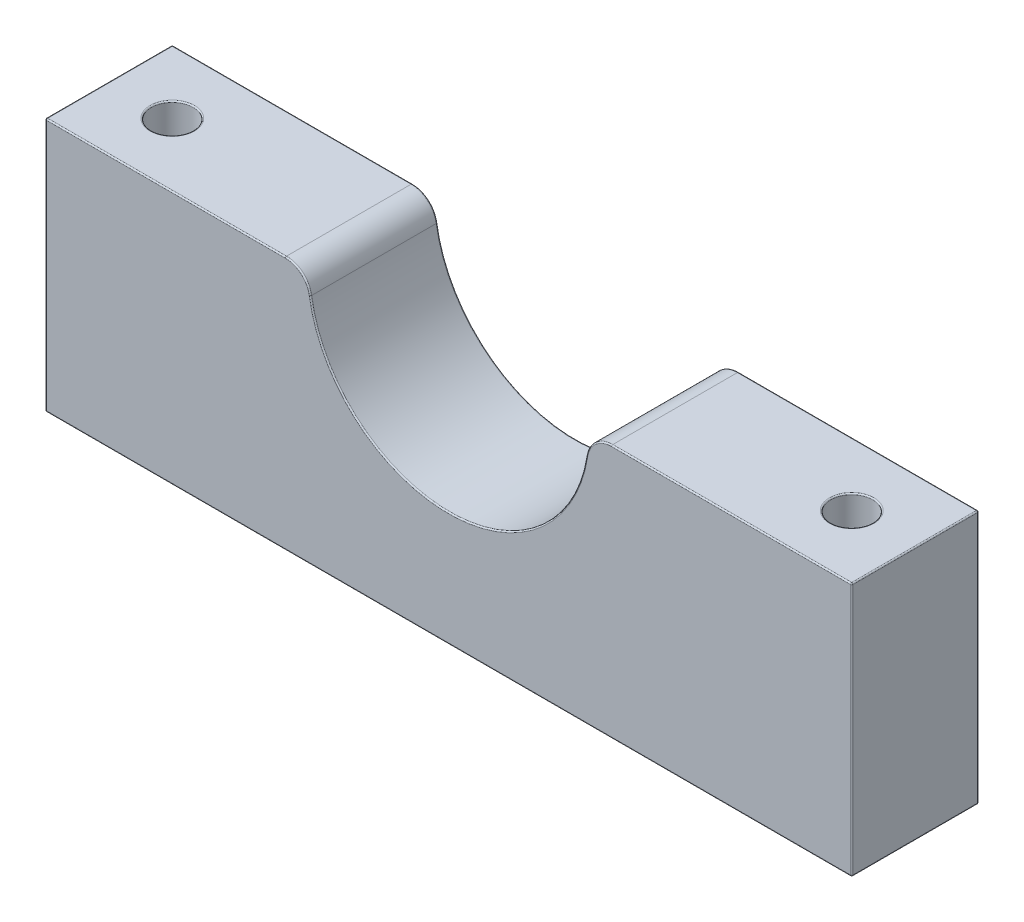
SolidWorks part; units mm, degrees
ref_plane "Спереди" through (0, 0, 0) normal (0, 0, 1) x (1, 0, 0)
ref_plane "Сверху" through (0, 0, 0) normal (0, 1, 0) x (1, 0, 0)
ref_plane "Справа" through (0, 0, 0) normal (1, 0, 0) x (0, 0, -1)
sketch "Эскиз1" plane through (0, 0, 0) normal (0, 0, 1) x (1, 0, 0)
  line L0 (0, 24.9844) -> (0, -42.4233) construction
  line L1 (11, 0) -> (31.75, 0)
  line L2 (-31.75, 0) -> (-11, 0)
  line L3 (-31.75, 0) -> (-31.75, -20)
  line L4 (-31.75, -20) -> (31.75, -20)
  line L5 (31.75, 0) -> (31.75, -20)
  line L6 (-31.75, 0) -> (31.75, -20) construction
  line L7 (-31.75, -20) -> (31.75, 0) construction
  arc A0 (-11, 0) -> (11, 0) centre (0, 0) ccw
  point P5 (0, -10)
  dimension "D1" = 22
  dimension "D2" = 63.5
  dimension "D3" = 20
extrude "Бобышка-Вытянуть1" add sketch "Эскиз1" along normal blind 10
sketch "Эскиз2" plane through (0, -20, 0) normal (0, -1, 0) x (1, 0, 0)
  line L0 (-31.75, 5) -> (31.75, 5) construction
  line L1 (-31.75, 10) -> (-31.75, 0) construction
  line L2 (31.75, 10) -> (31.75, 0) construction
  line L3 (-26.75, 10) -> (-26.75, 0) construction
  line L4 (-31.75, 10) -> (31.75, 10) construction
  line L5 (-31.75, 0) -> (31.75, 0) construction
  line L6 (26.75, 10) -> (26.75, 0) construction
  dimension "D1" = 5
  dimension "D2" = 5
hole_wizard "Отверстие обработанное метчиком M4x0.71" positions "Эскиз4" profile "Эскиз3" tap size "M4x0.7" standard "Ansi Metric" end condition through all
sketch "Эскиз4" plane through (0, -20, 0) normal (0, -1, 0) x (-1, 0, 0)
  line L0 (26.75, -10) -> (26.75, 0) construction
  line L1 (-26.75, -10) -> (-26.75, 0) construction
  point P0 (26.75, -5)
  point P4 (-26.75, -5)
sketch "Эскиз3" plane through (-26.75, -20, 5) normal (1, 0, 0) x (0, 0, -1)
  line L0 (0, 0) -> (0, 20)
  line L1 (0, 20) -> (1.65, 20)
  line L2 (1.65, 20) -> (1.65, 0)
  line L5 (1.65, 0) -> (0, 0)
  line L11 (0, -6.35) -> (0, 107.95) construction
  dimension "Диаметр проходного сверла" = 3.3
  dimension "Глубина проходного сверла" = 20
cosmetic thread "Отверстие резьбы1" parameters "D2"=4
cosmetic thread "Отверстие резьбы2" parameters "D2"=4
fillet "Скругление2" radius 2 2 edges at (11, 0, 5) (-11, 0, 5)
fillet "Скругление1" radius 0.1 24 edges at (31.75, 0, 5) (26.75, 0, 3.35) (-31.75, 0, 5) (-26.75, 0, 3.35) (-31.75, -20, 5) (31.75, -20, 5) (26.75, -20, 3.35) (-26.75, -20, 3.35) (-22.2976, 0, 0) (-31.75, -10, 0) (0, -20, 0) (31.75, -10, 0) (22.2976, 0, 0) (0, -11, 0) (22.2976, 0, 10) (31.75, -10, 10) (0, -20, 10) (-31.75, -10, 10) (-22.2976, 0, 10) (0, -11, 10) (-11.5443, -0.4809, 0) (11.5443, -0.4809, 0) (-11.5443, -0.4809, 10) (11.5443, -0.4809, 10)
